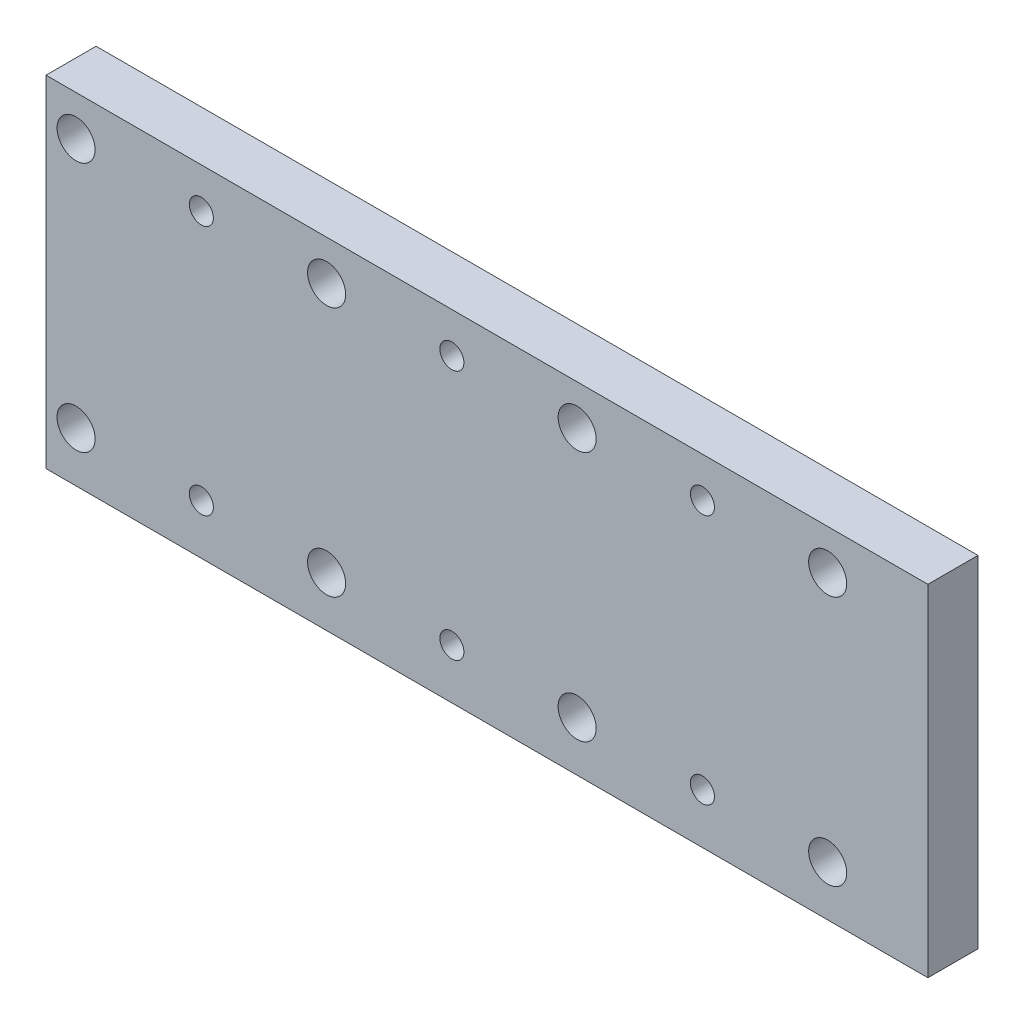
SolidWorks part; units mm, degrees
material "POM Acetal Copolymer"
ref_plane "Front Plane" through (0, 0, 0) normal (0, 0, 1) x (1, 0, 0)
ref_plane "Top Plane" through (0, 0, 0) normal (0, 1, 0) x (1, 0, 0)
ref_plane "Right Plane" through (0, 0, 0) normal (1, 0, 0) x (0, 0, -1)
sketch "Sketch1" plane through (0, 0, 0) normal (0, 0, 1) x (1, 0, 0)
  line L1 (-220, 85) -> (220, 85)
  line L2 (-220, 85) -> (-220, -85)
  line L3 (-220, -85) -> (220, -85)
  line L4 (220, 85) -> (220, -85)
  line L5 (-220, 85) -> (220, -85) construction
  line L6 (-220, -85) -> (220, 85) construction
  point P0 (0, 0)
  dimension "D1" = 440
  dimension "D2" = 170
extrude "Boss-Extrude1" add sketch "Sketch1" along normal blind 25
sketch "Sketch2" plane through (0, 0, 25) normal (0, 0, 1) x (1, 0, 0)
  line L0 (-220, -85) -> (220, -85) construction
  line L5 (-220, 85) -> (-220, -85) construction
  line L6 (-220, 0) -> (220, 0) construction
  line L7 (220, -85) -> (220, 85) construction
  line L37 (0, -85) -> (0, 85) construction
  line L42 (220, 85) -> (-220, 85) construction
  circle A20 centre (170, 65) radius 9.5
  circle A21 centre (45, 65) radius 9.5
  circle A22 centre (-80, 65) radius 9.5
  circle A23 centre (-205, 65) radius 9.5
  circle A24 centre (45, -60) radius 9.5
  circle A25 centre (-80, -60) radius 9.5
  circle A26 centre (-205, -60) radius 9.5
  circle A27 centre (170, -60) radius 9.5
  dimension "D10" = 19
  dimension "D2" = 4
  dimension "D3" = 2
  dimension "D4" = 125
  dimension "D6" = 50
  dimension "D11" = 20
  dimension "D12" = 50
  dimension "D5" = 125
extrude "Cut-Extrude1" cut sketch "Sketch2" against normal blind 15
sketch "Sketch4" plane through (0, 0, 10) normal (0, 0, 1) x (1, 0, 0)
  line L1 (170, -60) -> (170, 65) construction
  circle A0 centre (170, 65) radius 6
  circle A1 centre (45, 65) radius 6
  circle A2 centre (-80, 65) radius 6
  circle A3 centre (-205, 65) radius 6
  circle A4 centre (45, -60) radius 6
  circle A5 centre (-80, -60) radius 6
  circle A6 centre (-205, -60) radius 6
  circle A7 centre (170, -60) radius 6
  dimension "D1" = 12
  dimension "D4" = 125
  dimension "D5" = 125
  dimension "D2" = 4
  dimension "D3" = 2
extrude "Cut-Extrude3" cut sketch "Sketch4" against normal through all
sketch "Sketch3" plane through (0, 0, 0) normal (0, 0, -1) x (-1, 0, 0)
  line L5 (-170, -60) -> (-45, -60) construction
  circle A16 centre (-107.5, -60) radius 9.5
  circle A17 centre (17.5, -60) radius 9.5
  circle A18 centre (142.5, -60) radius 9.5
  circle A19 centre (17.5, 65) radius 9.5
  circle A20 centre (142.5, 65) radius 9.5
  circle A21 centre (-107.5, 65) radius 9.5
  dimension "D1" = 19
  dimension "D2" = 2
extrude "Cut-Extrude2" cut sketch "Sketch3" against normal blind 15
sketch "Sketch5" plane through (0, 0, 15) normal (0, 0, -1) x (-1, 0, 0)
  line L0 (-170, 65) -> (-45, 65) construction
  circle A0 centre (-107.5, -60) radius 6
  circle A1 centre (17.5, -60) radius 6
  circle A2 centre (142.5, -60) radius 6
  circle A3 centre (17.5, 65) radius 6
  circle A4 centre (142.5, 65) radius 6
  circle A5 centre (-107.5, 65) radius 6
  point P17 (-127.5, 65)
  point P18 (-127.5, 65)
  dimension "D1" = 12
  dimension "D3" = 125
  dimension "D2" = 2
extrude "Cut-Extrude4" cut sketch "Sketch5" against normal through all
sketch3d "3DSketch1"
  point P0 (-220, 85, -2.5)
